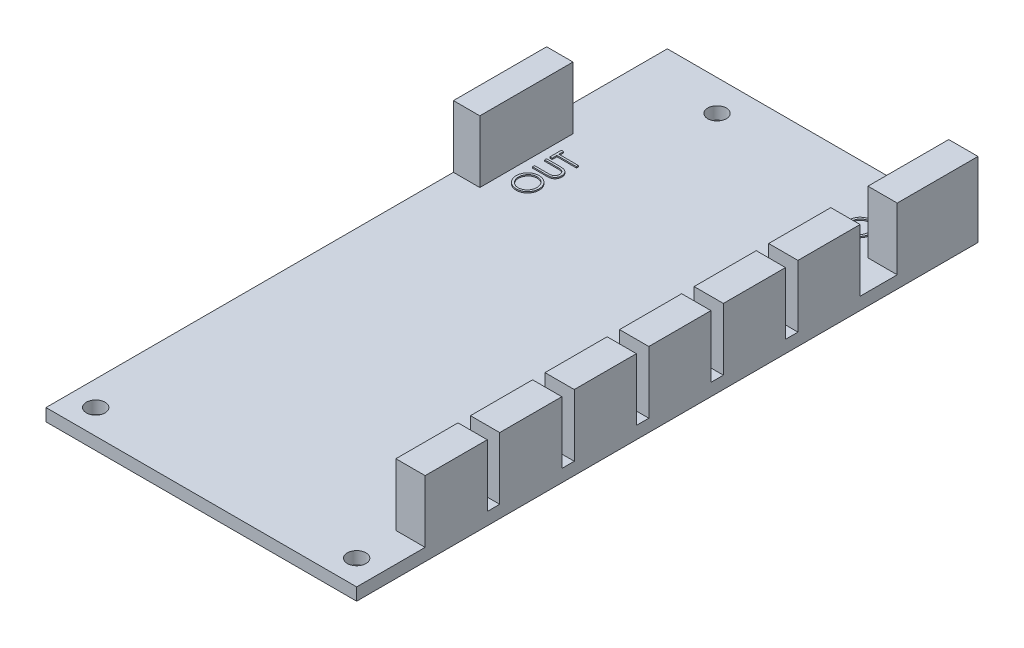
SolidWorks part; units mm, degrees
ref_plane "Ebene vorne" through (0, 0, 0) normal (0, 0, 1) x (1, 0, 0)
ref_plane "Ebene oben" through (0, 0, 0) normal (0, 1, 0) x (1, 0, 0)
ref_plane "Ebene rechts" through (0, 0, 0) normal (1, 0, 0) x (0, 0, -1)
sketch "Skizze1" plane through (0, 0, 0) normal (0, 1, 0) x (1, 0, 0)
  line L0 (0, 0) -> (0, -54812.6772) construction
  line L1 (0, 0) -> (54812.6772, 0) construction
  line L2 (-25, 45) -> (25, 45) construction
  line L3 (-25, -50) -> (25, -50)
  line L4 (-25, -50) -> (-25, 50)
  line L5 (-25, 50) -> (25, 50)
  line L6 (25, -50) -> (25, 50)
  line L7 (-25, -50) -> (25, 50) construction
  line L8 (-25, 50) -> (25, -50) construction
  circle A0 centre (-21, -46) radius 1.5
  circle A1 centre (21, -46) radius 1.5
  circle A2 centre (-12, 45) radius 1.5
  point P5 (0, 0)
  dimension "D3" = 42
  dimension "D4" = 3
  dimension "D7" = 13
  dimension "D1" = 50
  dimension "D2" = 100
  dimension "D5" = 4
  dimension "D6" = 91
extrude "Aufsatz-Linear austragen1" add sketch "Skizze1" along normal blind 2
sketch "Skizze2" plane through (0, 2, 0) normal (0, 1, 0) x (1, 0, 0)
  line L0 (-25, 50) -> (-25, -50) construction
  line L1 (-25, 30.5707) -> (-20.749, 30.5707)
  line L2 (-25, 30.5707) -> (-25, 15.5707)
  line L3 (-25, 15.5707) -> (-20.749, 15.5707)
  line L4 (-20.749, 30.5707) -> (-20.749, 15.5707)
  line L5 (25, -50) -> (25, 50) construction
  line L6 (25, 50) -> (20.2897, 50)
  line L7 (25, 50) -> (25, 37)
  line L8 (25, 37) -> (20.2897, 37)
  line L9 (20.2897, 50) -> (20.2897, 37)
  line L10 (25, 31.02) -> (20.2897, 31.02)
  line L11 (25, 31.02) -> (25, 21.02)
  line L12 (25, 21.02) -> (20.2897, 21.02)
  line L13 (20.2897, 31.02) -> (20.2897, 21.02)
  line L14 (25, 19.02) -> (20.2897, 19.02)
  line L15 (25, 19.02) -> (25, 9.02)
  line L16 (25, 9.02) -> (20.2897, 9.02)
  line L17 (20.2897, 19.02) -> (20.2897, 9.02)
  line L18 (25, 7.02) -> (20.2897, 7.02)
  line L19 (25, 7.02) -> (25, -2.98)
  line L20 (25, -2.98) -> (20.2897, -2.98)
  line L21 (20.2897, 7.02) -> (20.2897, -2.98)
  line L22 (25, -4.98) -> (20.2897, -4.98)
  line L23 (25, -4.98) -> (25, -14.98)
  line L24 (25, -14.98) -> (20.2897, -14.98)
  line L25 (20.2897, -4.98) -> (20.2897, -14.98)
  line L26 (25, -16.98) -> (20.2897, -16.98)
  line L27 (25, -16.98) -> (25, -26.98)
  line L28 (25, -26.98) -> (20.2897, -26.98)
  line L29 (20.2897, -16.98) -> (20.2897, -26.98)
  line L30 (25, -28.98) -> (20.2897, -28.98)
  line L31 (25, -28.98) -> (25, -38.98)
  line L32 (25, -38.98) -> (20.2897, -38.98)
  line L33 (20.2897, -28.98) -> (20.2897, -38.98)
  dimension "D1" = 15
  dimension "D2" = 13
  dimension "D3" = 10
  dimension "D4" = 6
extrude "Aufsatz-Linear austragen2" add sketch "Skizze2" along normal blind 10
sketch "Skizze3" plane through (0, 2, 0) normal (0, 1, 0) x (1, 0, 0)
  line L0 (13.7573, 50) -> (13.7573, 37.9395) construction
  line L1 (20.2897, 50) -> (-25, 50) construction
  line L2 (13.7573, 31.4211) -> (13.7573, -40.1564) construction
  line L4 (-15.6918, 14.8346) -> (-15.6918, 30.2045) construction
  text T0 "VCC"
  text T1 "MEASUREMENT INPUTS"
  text T2 "OUT"
extrude "Aufsatz-Linear austragen3" add sketch "Skizze3" along normal blind 0.2
